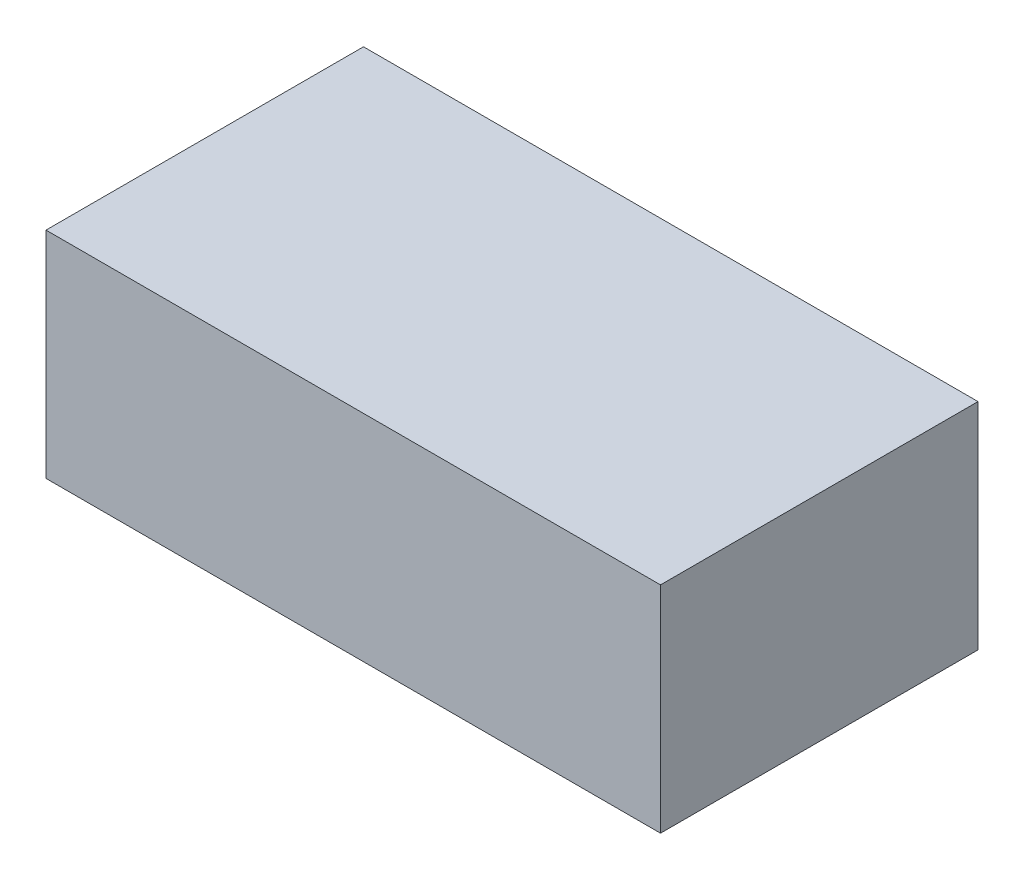
SolidWorks part; units mm, degrees
ref_plane "Front Plane" through (0, 0, 0) normal (0, 0, 1) x (1, 0, 0)
ref_plane "Top Plane" through (0, 0, 0) normal (0, 1, 0) x (1, 0, 0)
ref_plane "Right Plane" through (0, 0, 0) normal (1, 0, 0) x (0, 0, -1)
sketch "Sketch1" plane through (0, 0, 0) normal (0, 1, 0) x (1, 0, 0)
  line L1 (0, 0) -> (60, 0)
  line L2 (0, 0) -> (0, 31.0001)
  line L3 (0, 31.0001) -> (60, 31.0001)
  line L4 (60, 0) -> (60, 31.0001)
  dimension "D1" = 60
  dimension "D2" = 31.0001
extrude "Boss-Extrude1" add sketch "Sketch1" along normal blind 21
equation "\"D1@Sketch1\"=60mm"
equation "\"D2@Sketch1\"=31.0001mm"
equation "\"D1@Boss-Extrude1\"=21mm"
